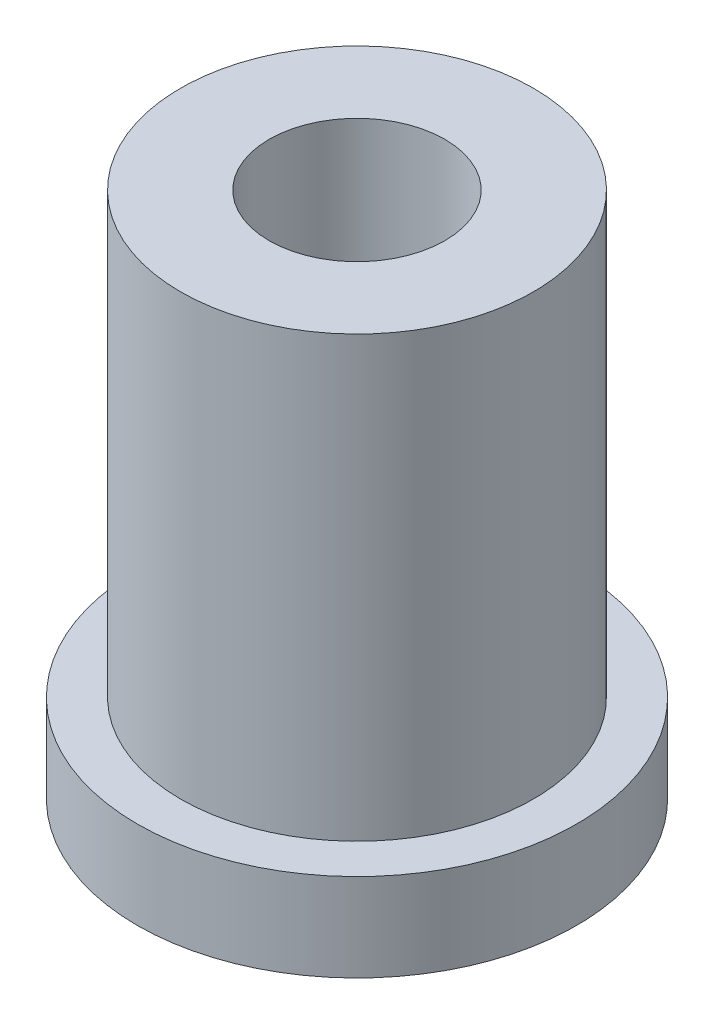
SolidWorks part; units mm, degrees
ref_plane "Front" through (0, 0, 0) normal (0, 0, 1) x (1, 0, 0)
ref_plane "Top" through (0, 0, 0) normal (0, 1, 0) x (1, 0, 0)
ref_plane "Right" through (0, 0, 0) normal (1, 0, 0) x (0, 0, -1)
sketch "Sketch1" plane through (0, 0, 0) normal (0, 1, 0) x (1, 0, 0)
  circle A0 centre (0, 0) radius 1.5875
  circle A1 centre (0, 0) radius 3.1877
  circle A2 centre (0, 0) radius 3.9688
  dimension "ID" = 3.175
  dimension "OD" = 6.3754
  dimension "FlangeOD" = 7.9375
sketch "Sketch2" plane through (0, 0, 0) normal (0, 1, 0) x (1, 0, 0)
  circle A0 centre (0, 0) radius 1.5875 construction
  circle A1 centre (0, 0) radius 3.1877 construction
  circle A2 centre (0, 0) radius 1.5875
  circle A3 centre (0, 0) radius 3.1877
extrude "Boss-Extrude1" add sketch "Sketch2" along normal blind 9.525
sketch "Sketch3" plane through (0, 0, 0) normal (0, 1, 0) x (1, 0, 0)
  circle A0 centre (0, 0) radius 3.9688 construction
  circle A1 centre (0, 0) radius 3.1877 construction
  circle A2 centre (0, 0) radius 3.9688
  circle A3 centre (0, 0) radius 3.1877
extrude "Boss-Extrude2" add sketch "Sketch3" along normal blind 1.5875
